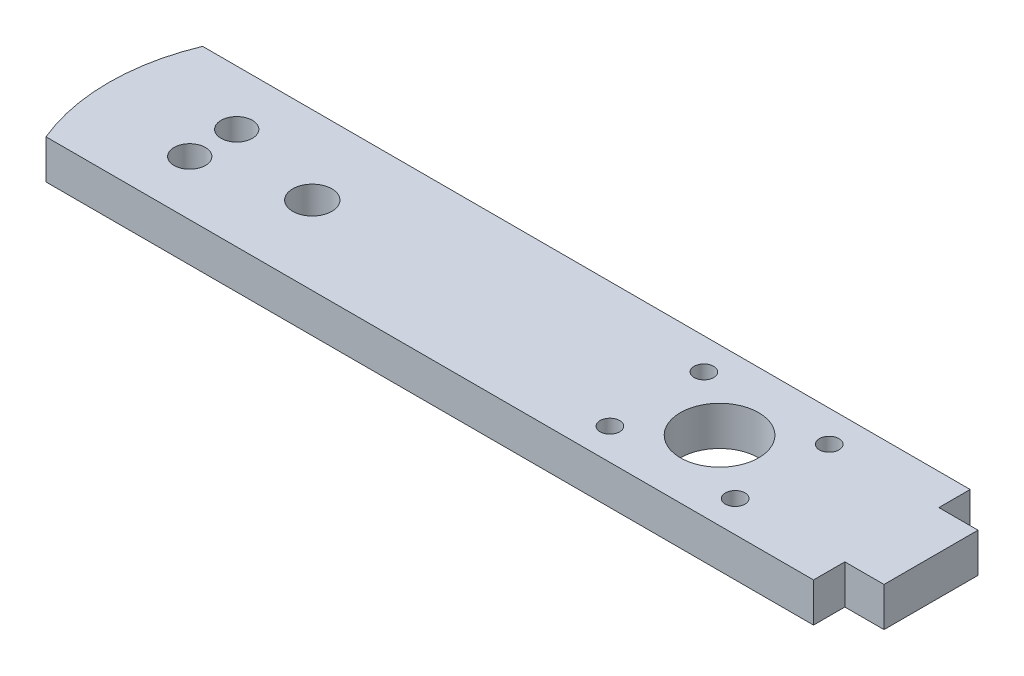
SolidWorks part; units mm, degrees
material "AISI 304"
ref_plane "Front Plane" through (0, 0, 0) normal (0, 0, 1) x (1, 0, 0)
ref_plane "Top Plane" through (0, 0, 0) normal (0, 1, 0) x (1, 0, 0)
ref_plane "Right Plane" through (0, 0, 0) normal (1, 0, 0) x (0, 0, -1)
sketch "Sketch1" plane through (0, 0, 0) normal (0, 1, 0) x (1, 0, 0)
  line L0 (0, 0) -> (70, 0) construction
  line L1 (-70, -10) -> (70, -10)
  line L2 (-70, -10) -> (-70, 10)
  line L3 (-70, 10) -> (70, 10)
  line L4 (70, -10) -> (70, 10)
  line L5 (-70, -10) -> (70, 10) construction
  line L6 (-70, 10) -> (70, -10) construction
  line L7 (70, 6) -> (75, 6)
  line L8 (70, 6) -> (70, -6)
  line L9 (70, -6) -> (75, -6)
  line L10 (75, 6) -> (75, -6)
  line L11 (70, 6) -> (75, -6) construction
  line L12 (70, -6) -> (75, 6) construction
  line L13 (70, 0) -> (75, 0) construction
  point P0 (0, 0)
  point P6 (72.5, 0)
  dimension "D1" = 5
  dimension "D2" = 12
  dimension "D3" = 140
  dimension "D4" = 20
extrude "Boss-Extrude1" add sketch "Sketch1" along normal mid plane 5 contours L1 L4 L3 L2 | L9 L10 L7 L8
sketch "Sketch2" plane through (0, -2.5, 0) normal (0, -1, 0) x (1, 0, 0)
  line L0 (2.75, 0) -> (-2.75, 0) construction
  line L2 (75, -6) -> (75, 6) construction
  circle A0 centre (48, 0) radius 5
  point P4 (75, 0)
  dimension "D1" = 10
  dimension "D2" = 27
extrude "Cut-Extrude1" cut sketch "Sketch2" against normal blind 5
sketch "Sketch3" plane through (0, 0, 0) normal (0, 1, 0) x (1, 0, 0)
  line L0 (75, 6) -> (75, -6) construction
  line L1 (56, -6) -> (40, -6)
  line L2 (56, -6) -> (56, 6)
  line L3 (56, 6) -> (40, 6)
  line L4 (40, -6) -> (40, 6)
  line L5 (56, -6) -> (40, 6) construction
  line L6 (56, 6) -> (40, -6) construction
  line L7 (70, 6) -> (75, 6) construction
  point P0 (48, 0)
  dimension "D1" = 19
hole_wizard "M3 Tapped Hole2" positions "Sketch14" profile "Sketch15" tap size "M3" standard "ISO" end condition through all
sketch "Sketch14" plane through (0, -2.5, 0) normal (0, -1, 0) x (-1, 0, 0)
  point P0 (-56, 6)
  point P3 (-40, 6)
  point P6 (-40, -6)
  point P9 (-56, -6)
sketch "Sketch15" plane through (56, -2.5, -6) normal (1, 0, 0) x (0, 0, -1)
  line L0 (0, 0) -> (0, 5)
  line L1 (0, 5) -> (1.25, 5)
  line L2 (1.25, 5) -> (1.25, 0.275)
  line L3 (1.25, 0.275) -> (1.525, 0)
  line L5 (1.525, 0) -> (0, 0)
  line L6 (-1.25, 0.275) -> (-1.525, 0) construction
  line L11 (0, -6.35) -> (0, 107.95) construction
  dimension "Thru Tap Drill Dia." = 2.5
  dimension "Thru Tap Drill Depth" = 5
  dimension "Near C'Sink Dia." = 3.05
  dimension "Near C'Sink Angle" = 90
cosmetic thread "Hole Thread9" parameters "D2"=3
cosmetic thread "Hole Thread10" parameters "D2"=3
cosmetic thread "Hole Thread11" parameters "D2"=3
cosmetic thread "Hole Thread12" parameters "D2"=3
hole_wizard "Ø5.0mm Dowel Hole1" positions "Sketch16" profile "Sketch17" hole size "Ø5.0" standard "ISO" end condition through all
sketch "Sketch16" plane through (0, -2.5, 0) normal (0, -1, 0) x (-1, 0, 0)
  line L0 (-2.75, 0) -> (2.75, 0) construction
  line L1 (-75, 6) -> (-75, -6) construction
  point P0 (4, 0)
  dimension "D1" = 79
sketch "Sketch17" plane through (-4, -2.5, 0) normal (1, 0, 0) x (0, 0, -1)
  line L0 (0, 0) -> (0, 5)
  line L1 (0, 5) -> (2.5, 5)
  line L2 (2.5, 5) -> (2.5, 0)
  line L5 (2.5, 0) -> (0, 0)
  line L11 (0, -6.35) -> (0, 107.95) construction
  dimension "Thru Hole Dia." = 5
  dimension "Thru Hole Depth" = 5
sketch "Sketch18" plane through (0, 2.5, 0) normal (0, 1, 0) x (1, 0, 0)
  line L0 (-2.75, 0) -> (2.75, 0) construction
  circle A0 centre (-4, 0) radius 13
  point P3 (-16.6491, 3)
  point P4 (-16.6491, -3)
  dimension "D1" = 26
  dimension "D2" = 3
  dimension "D3" = 3
hole_wizard "CBORE for M5 Hex Head Bolt2" positions "3DSketch9" profile "Sketch28" counterbore size "M5" standard "ISO" end condition through all
sketch3d "3DSketch9"
  point P0 (-16.6491, 2.5, 3)
  point P3 (-16.6491, 2.5, -3)
sketch "Sketch28" plane through (-16.6491, 2.5, 3) normal (1, 0, 0) x (0, 0, 1)
  line L0 (0, 0) -> (0, 5)
  line L1 (0, 5) -> (1.5, 5)
  line L3 (1.5, 5) -> (1.5, 3)
  line L4 (1.5, 3) -> (2, 3)
  line L5 (2, 3) -> (2, 0)
  line L7 (2, 0) -> (0, 0)
  line L11 (0, -6.35) -> (0, 107.95) construction
  dimension "Thru Hole Dia." = 3
  dimension "Thru Hole Depth" = 5
  dimension "C'Bore Dia." = 4
  dimension "C'Bore Depth" = 3
sketch "Sketch29" plane through (0, 2.5, 0) normal (0, 1, 0) x (1, 0, 0)
  circle A0 centre (-4, 0) radius 26
  line M9 (-70, 10) -> (-70, -10)
  line M10 (-70, -10) -> (70, -10)
  line M16 (70, 10) -> (-70, 10)
  dimension "D1" = 52
extrude "Cut-Extrude2" cut sketch "Sketch29" against normal blind 10 contours A0 M16 M9 M10
